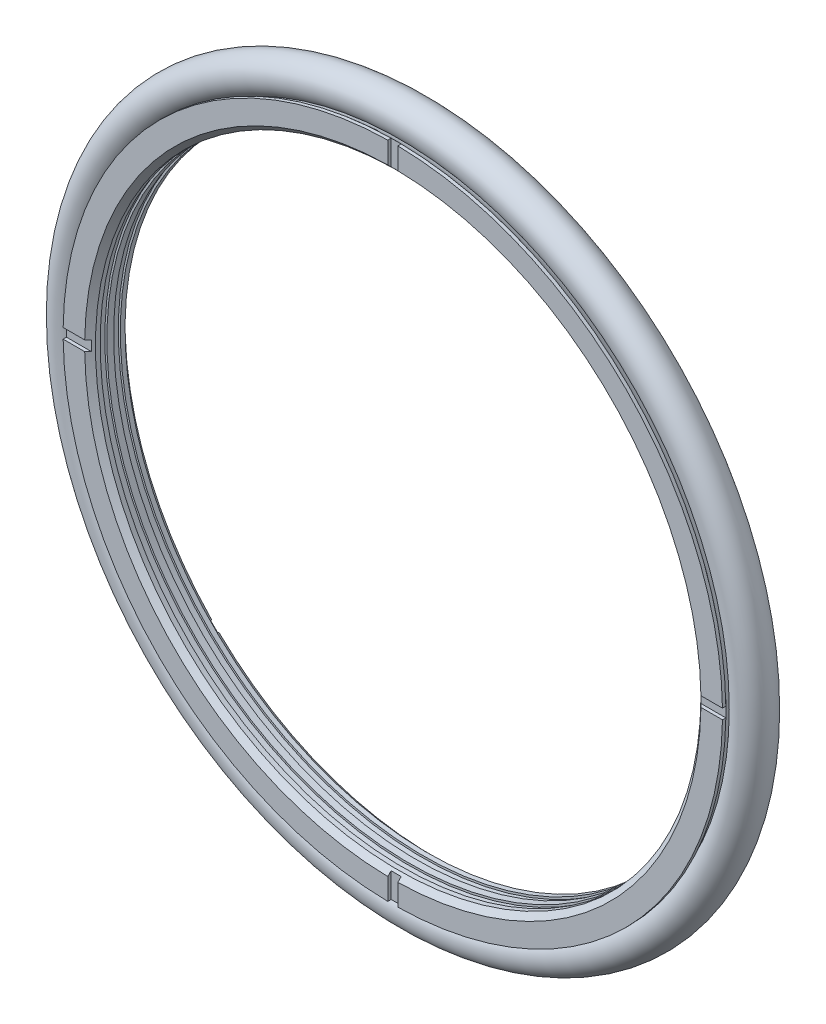
SolidWorks part; units mm, degrees
material "PTFE+NBR"
ref_plane "Front Plane" through (0, 0, 0) normal (0, 0, 1) x (1, 0, 0)
ref_plane "Top Plane" through (0, 0, 0) normal (0, 1, 0) x (1, 0, 0)
ref_plane "Right Plane" through (0, 0, 0) normal (1, 0, 0) x (0, 0, -1)
sketch "Sketch1" plane through (0, 0, 0) normal (1, 0, 0) x (0, 0, -1)
  line L0 (0, 0) -> (70.1333, 0) construction
  line L1 (0, 0) -> (0, 74.4081) construction
  line L2 (-2.2, 45) -> (-1.5, 45)
  line L3 (3, 45.8) -> (3, 49)
  line L4 (3, 49) -> (2.5, 49)
  line L5 (-3, 49) -> (-2.5, 49)
  line L6 (-3, 45.8) -> (-3, 49)
  line L7 (-1.5, 45) -> (-1.5, 45.3)
  line L8 (-1.5, 45.3) -> (-0.5, 45.3)
  line L9 (-0.5, 45.3) -> (-0.5, 45)
  line L10 (1.5, 45) -> (2.2, 45)
  line L11 (-2.2, 45) -> (-3, 45.8)
  line L12 (2.2, 45) -> (3, 45.8)
  line L13 (-0.5, 45) -> (0.5, 45)
  line L14 (0.5, 45.3) -> (0.5, 45)
  line L15 (1.5, 45.3) -> (0.5, 45.3)
  line L16 (1.5, 45) -> (1.5, 45.3)
  arc A0 (-2.5, 49) -> (2.5, 49) centre (0, 50.7626) ccw
  point P5 (3, 45)
  point P10 (-3, 45)
  point P11 (0, 60)
  point P25 (0, 45)
  dimension "D6" = 3.0589
  dimension "D5" = 1
  dimension "D14" = 2.7037
  dimension "D1" = 6
  dimension "D2" = 6
  dimension "D3" = 90
  dimension "D4" = 98
  dimension "D7" = 1
  dimension "D8" = 0.8
  dimension "D9" = 45
  dimension "D10" = 0.8
  dimension "D11" = 45
  dimension "D12" = 0.3
  dimension "D13" = 5
revolve "Revolve1" add sketch "Sketch1" angle 360 about L0
sketch "Sketch4" plane through (0, 0, 3) normal (0, 0, 1) x (1, 0, 0)
  line L0 (0, 0) -> (0, 54.67) construction
  line L1 (-0.75, 50.4268) -> (0.75, 50.4268)
  line L2 (-0.75, 50.4268) -> (-0.75, 43.977)
  line L3 (-0.75, 43.977) -> (0.75, 43.977)
  line L4 (0.75, 50.4268) -> (0.75, 43.977)
  dimension "D1" = 1.5
  dimension "D2" = 43.977
  dimension "D3" = 6.4498
extrude "Cut-Extrude1" cut sketch "Sketch4" against normal blind 0.5
sketch "Sketch5" plane through (0, 0, -3) normal (0, 0, -1) x (-1, 0, 0)
  line L0 (0, 0) -> (40.9381, 40.9381) construction
  line L1 (0, 0) -> (61.4907, 0) construction
  line L2 (36.9226, 35.862) -> (35.862, 36.9226)
  line L3 (35.862, 36.9226) -> (28.2441, 29.3048)
  line L4 (28.2441, 29.3048) -> (29.3048, 28.2441)
  line L5 (36.9226, 35.862) -> (29.3048, 28.2441)
  point P9 (28.7745, 28.7745)
  point P10 (36.3923, 36.3923)
  dimension "D1" = 45
  dimension "D2" = 1.5
  dimension "D3" = 10.7732
  dimension "D4" = 40.6932
extrude "Cut-Extrude2" cut sketch "Sketch5" against normal blind 0.5
pattern_circular "CirPattern1" count 4 over 360 about axis through (0, 0, 0) along (0, 0, 1) of "Cut-Extrude1", "Cut-Extrude2"
sketch "Sketch2" plane through (0, 0, 0) normal (1, 0, 0) x (0, 0, -1)
  line L0 (0, 0) -> (29.2798, 0) construction
  circle A0 centre (0, 50.75) radius 2.65
  dimension "D1" = 106.8
  dimension "D2" = 5.3
revolve "Revolve2" add sketch "Sketch2" angle 360 about L0
